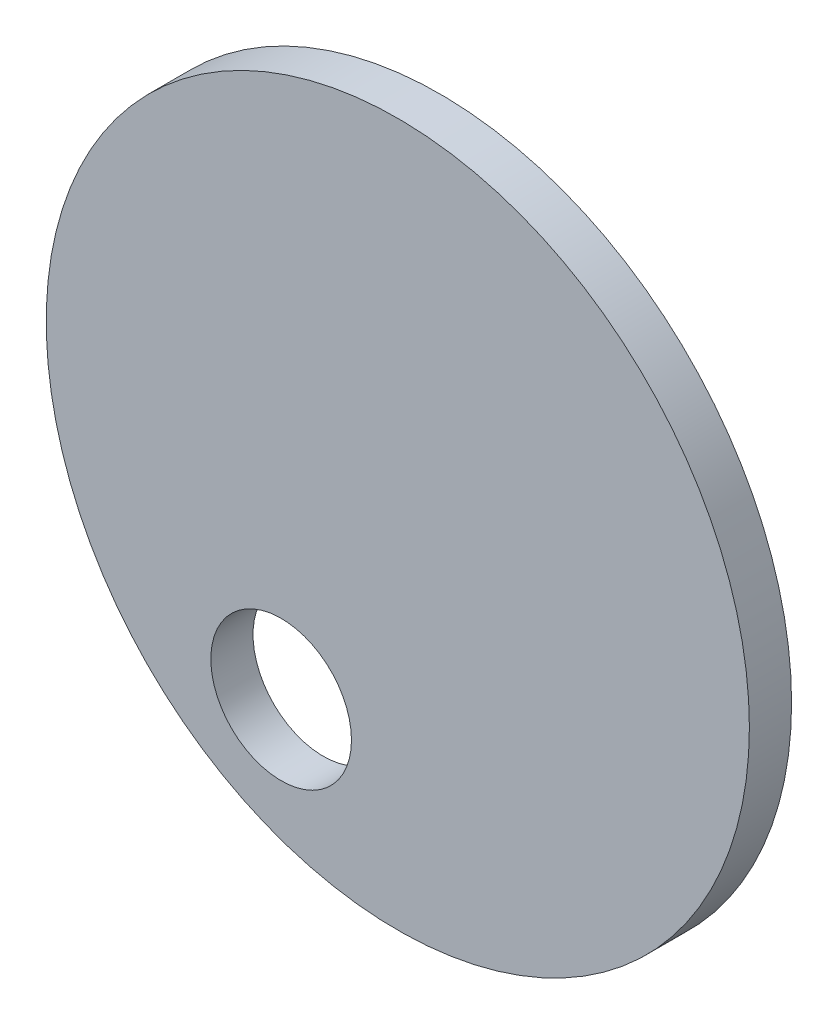
SolidWorks part; units mm, degrees
material "Plastique personnalisé"
ref_plane "Plan de face" through (0, 0, 0) normal (0, 0, 1) x (1, 0, 0)
ref_plane "Plan de dessus" through (0, 0, 0) normal (0, 1, 0) x (1, 0, 0)
ref_plane "Plan de droite" through (0, 0, 0) normal (1, 0, 0) x (0, 0, -1)
sketch "Esquisse1" plane through (0, 0, 0) normal (0, 0, 1) x (1, 0, 0)
  circle A0 centre (0, 0) radius 25
  dimension "D1" = 50
extrude "Boss.-Extru.1" add sketch "Esquisse1" along normal blind 3
sketch "Esquisse3" plane through (0, 0, 0) normal (0, 0, -1) x (-1, 0, 0)
  line L0 (-1.3973, 1.5) -> (1.3973, 1.5)
  circle A0 centre (0, 0) radius 6
  arc A1 (-1.3973, 1.5) -> (1.3973, 1.5) centre (0, 0) ccw
  dimension "D1" = 12
  dimension "D2" = 4.1
  dimension "D3" = 1.5
extrude "Boss.-Extru.3" add sketch "Esquisse3" along normal blind 9
sketch "Esquisse4" plane through (0, 0, 3) normal (0, 0, 1) x (1, 0, 0)
  circle A0 centre (-8.2954, -14.9409) radius 5
  dimension "D1" = 10
  dimension "D2" = 8.2954
  dimension "D3" = 14.9409
extrude "Enlèv. mat.-Extru.2" cut sketch "Esquisse4" against normal blind 5
